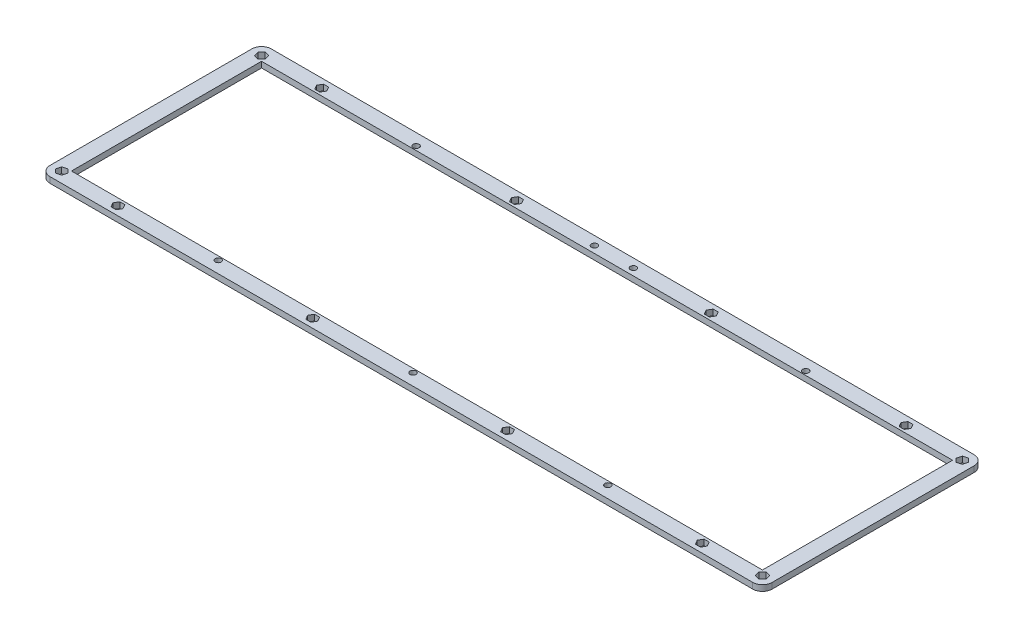
SolidWorks part; units mm, degrees
ref_plane "Front Plane" through (0, 0, 0) normal (0, 0, 1) x (1, 0, 0)
ref_plane "Top Plane" through (0, 0, 0) normal (0, 1, 0) x (1, 0, 0)
ref_plane "Right Plane" through (0, 0, 0) normal (1, 0, 0) x (0, 0, -1)
sketch "Sketch1" plane through (0, 0, 0) normal (0, 1, 0) x (1, 0, 0)
  line L0 (0, 108.6) -> (0, 5)
  line L1 (365.775, 0) -> (5, 0)
  line L2 (370.775, 108.6) -> (370.775, 5)
  line L3 (5, 113.6) -> (365.775, 113.6)
  line L4 (8, 8) -> (8, 105.6)
  line L5 (362.775, 8) -> (362.775, 105.6)
  line L6 (8, 8) -> (362.775, 8)
  line L7 (234.0885, 111.35) -> (236.6865, 111.35)
  line L8 (236.6865, 111.35) -> (237.9856, 109.1)
  line L9 (237.9856, 109.1) -> (236.6865, 106.85)
  line L10 (236.6865, 106.85) -> (234.0885, 106.85)
  line L11 (234.0885, 106.85) -> (232.7894, 109.1)
  line L12 (232.7894, 109.1) -> (234.0885, 111.35)
  line L13 (334.0885, 111.35) -> (336.6865, 111.35)
  line L14 (336.6865, 111.35) -> (337.9856, 109.1)
  line L15 (337.9856, 109.1) -> (336.6865, 106.85)
  line L16 (336.6865, 106.85) -> (334.0885, 106.85)
  line L17 (334.0885, 106.85) -> (332.7894, 109.1)
  line L18 (332.7894, 109.1) -> (334.0885, 111.35)
  line L19 (365.9474, 110.6096) -> (367.7845, 108.7724)
  line L20 (367.7845, 108.7724) -> (367.1121, 106.2629)
  line L21 (367.1121, 106.2629) -> (364.6026, 105.5905)
  line L22 (364.6026, 105.5905) -> (362.7654, 107.4276)
  line L23 (362.7654, 107.4276) -> (363.4379, 109.9371)
  line L24 (363.4379, 109.9371) -> (365.9474, 110.6096)
  line L25 (136.6865, 111.35) -> (134.0885, 111.35)
  line L26 (134.0885, 111.35) -> (132.7894, 109.1)
  line L27 (132.7894, 109.1) -> (134.0885, 106.85)
  line L28 (134.0885, 106.85) -> (136.6865, 106.85)
  line L29 (136.6865, 106.85) -> (137.9856, 109.1)
  line L30 (137.9856, 109.1) -> (136.6865, 111.35)
  line L31 (36.6865, 111.35) -> (34.0885, 111.35)
  line L32 (34.0885, 111.35) -> (32.7894, 109.1)
  line L33 (32.7894, 109.1) -> (34.0885, 106.85)
  line L34 (34.0885, 106.85) -> (36.6865, 106.85)
  line L35 (36.6865, 106.85) -> (37.9856, 109.1)
  line L36 (37.9856, 109.1) -> (36.6865, 111.35)
  line L37 (4.8276, 110.6096) -> (2.9904, 108.7724)
  line L38 (2.9904, 108.7724) -> (3.6629, 106.2629)
  line L39 (3.6629, 106.2629) -> (6.1724, 105.5905)
  line L40 (6.1724, 105.5905) -> (8.0095, 107.4276)
  line L41 (8.0095, 107.4276) -> (7.3371, 109.9371)
  line L42 (7.3371, 109.9371) -> (4.8276, 110.6096)
  line L43 (234.0885, 2.25) -> (236.6865, 2.25)
  line L44 (236.6865, 2.25) -> (237.9856, 4.5)
  line L45 (237.9856, 4.5) -> (236.6865, 6.75)
  line L46 (236.6865, 6.75) -> (234.0885, 6.75)
  line L47 (234.0885, 6.75) -> (232.7894, 4.5)
  line L48 (232.7894, 4.5) -> (234.0885, 2.25)
  line L49 (334.0885, 2.25) -> (336.6865, 2.25)
  line L50 (336.6865, 2.25) -> (337.9856, 4.5)
  line L51 (337.9856, 4.5) -> (336.6865, 6.75)
  line L52 (336.6865, 6.75) -> (334.0885, 6.75)
  line L53 (334.0885, 6.75) -> (332.7894, 4.5)
  line L54 (332.7894, 4.5) -> (334.0885, 2.25)
  line L55 (365.9474, 2.9905) -> (367.7845, 4.8276)
  line L56 (367.7845, 4.8276) -> (367.1121, 7.3371)
  line L57 (367.1121, 7.3371) -> (364.6026, 8.0096)
  line L58 (364.6026, 8.0096) -> (362.7654, 6.1724)
  line L59 (362.7654, 6.1724) -> (363.4379, 3.6629)
  line L60 (363.4379, 3.6629) -> (365.9474, 2.9905)
  line L61 (136.6865, 2.25) -> (134.0885, 2.25)
  line L62 (134.0885, 2.25) -> (132.7894, 4.5)
  line L63 (132.7894, 4.5) -> (134.0885, 6.75)
  line L64 (134.0885, 6.75) -> (136.6865, 6.75)
  line L65 (136.6865, 6.75) -> (137.9856, 4.5)
  line L66 (137.9856, 4.5) -> (136.6865, 2.25)
  line L67 (36.6865, 2.25) -> (34.0885, 2.25)
  line L68 (34.0885, 2.25) -> (32.7894, 4.5)
  line L69 (32.7894, 4.5) -> (34.0885, 6.75)
  line L70 (34.0885, 6.75) -> (36.6865, 6.75)
  line L71 (36.6865, 6.75) -> (37.9856, 4.5)
  line L72 (37.9856, 4.5) -> (36.6865, 2.25)
  line L73 (4.8276, 2.9905) -> (2.9904, 4.8276)
  line L74 (2.9904, 4.8276) -> (3.6629, 7.3371)
  line L75 (3.6629, 7.3371) -> (6.1724, 8.0096)
  line L76 (6.1724, 8.0096) -> (8.0095, 6.1724)
  line L77 (8.0095, 6.1724) -> (7.3371, 3.6629)
  line L78 (7.3371, 3.6629) -> (4.8276, 2.9905)
  line L79 (8, 105.6) -> (362.775, 105.6)
  arc A0 (365.775, 0) -> (370.775, 5) centre (365.775, 5) ccw
  arc A1 (370.775, 108.6) -> (365.775, 113.6) centre (365.775, 108.6) ccw
  arc A2 (0, 5) -> (5, 0) centre (5, 5) ccw
  arc A3 (5, 113.6) -> (0, 108.6) centre (5, 108.6) ccw
  circle A4 centre (195.3875, 109.1) radius 1.55
  circle A5 centre (175.3875, 109.1) radius 1.55
  circle A6 centre (85.3875, 107.6) radius 1.55
  circle A7 centre (285.3875, 107.6) radius 1.55
  circle A8 centre (85.3875, 6) radius 1.55
  circle A9 centre (185.3875, 6) radius 1.55
  circle A10 centre (285.3875, 6) radius 1.55
extrude "Boss-Extrude1" add sketch "Sketch1" against normal blind 3
